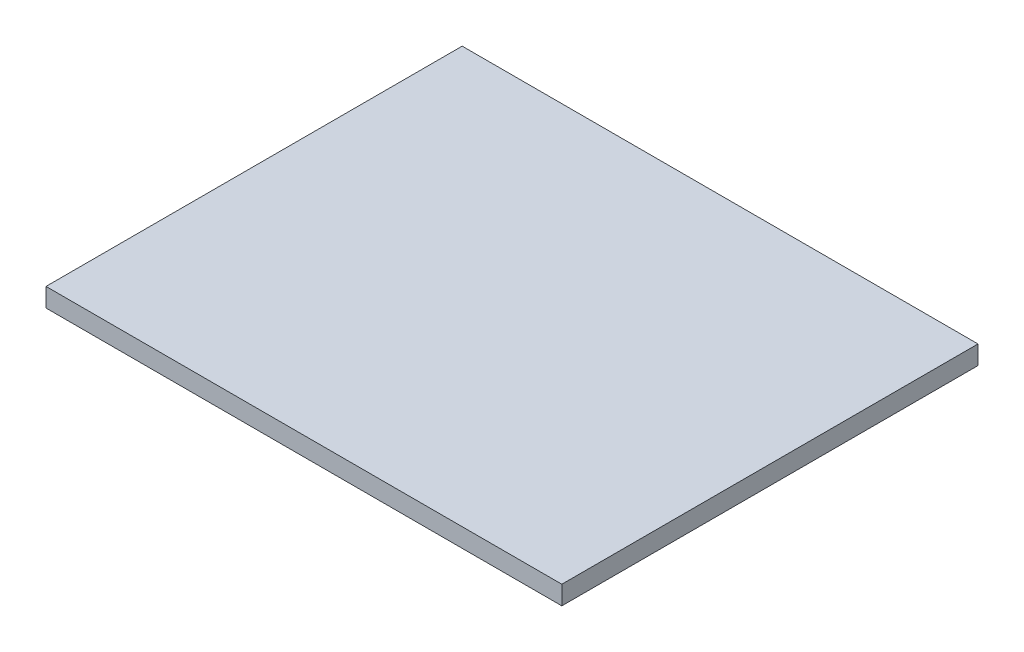
SolidWorks part; units mm, degrees
ref_plane "前视基准面" through (0, 0, 0) normal (0, 0, 1) x (1, 0, 0)
ref_plane "上视基准面" through (0, 0, 0) normal (0, 1, 0) x (1, 0, 0)
ref_plane "右视基准面" through (0, 0, 0) normal (1, 0, 0) x (0, 0, -1)
sketch "草图1" plane through (0, 0, 0) normal (0, 1, 0) x (1, 0, 0)
  line L1 (-22, -17.75) -> (22, -17.75)
  line L2 (-22, -17.75) -> (-22, 17.75)
  line L3 (-22, 17.75) -> (22, 17.75)
  line L4 (22, -17.75) -> (22, 17.75)
  line L5 (-22, -17.75) -> (22, 17.75) construction
  line L6 (-22, 17.75) -> (22, -17.75) construction
  point P0 (0, 0)
  dimension "D1" = 44
  dimension "D2" = 35.5
extrude "凸台-拉伸1" add sketch "草图1" along normal blind 1.6
